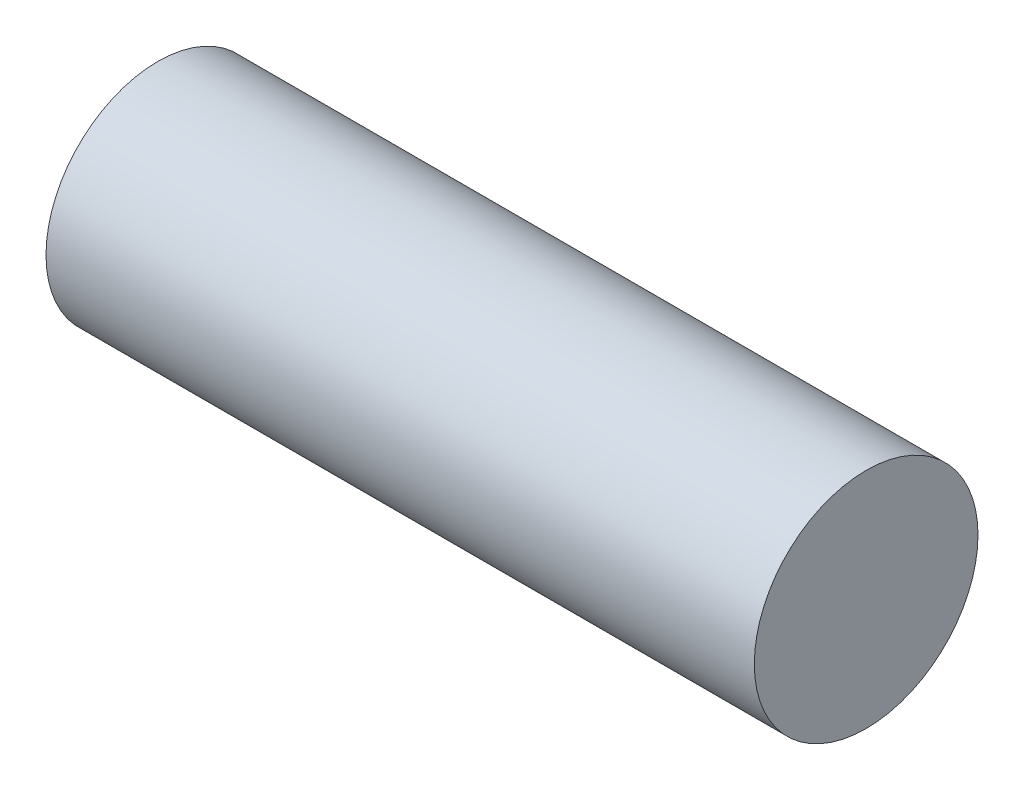
SolidWorks part; units mm, degrees
ref_plane "前视基准面" through (0, 0, 0) normal (0, 0, 1) x (1, 0, 0)
ref_plane "上视基准面" through (0, 0, 0) normal (0, 1, 0) x (1, 0, 0)
ref_plane "右视基准面" through (0, 0, 0) normal (1, 0, 0) x (0, 0, -1)
other "Configuration Table"
sketch "草图1" plane through (0, 0, 0) normal (0, 0, 1) x (1, 0, 0)
  line L0 (0, 0) -> (40.0305, 0) construction
  line L1 (0, 0) -> (0, 9)
  line L2 (0, 9) -> (57, 9)
  line L3 (57, 9) -> (57, 0)
  line L4 (0, 0) -> (57, 0)
  dimension "D1" = 9
  dimension "D2" = 57
revolve "旋转1" add sketch "草图1" angle 360 about L0
